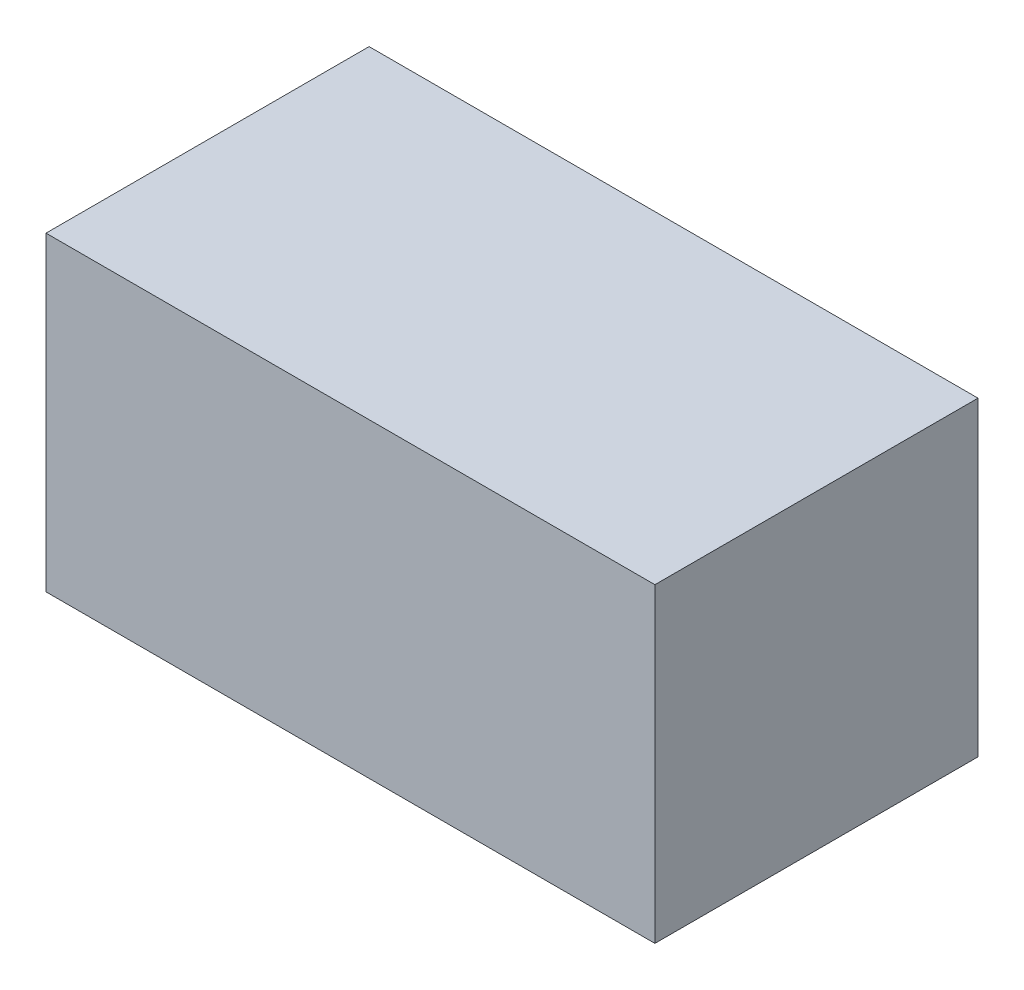
SolidWorks part; units mm, degrees
ref_plane "Front Plane" through (0, 0, 0) normal (0, 0, 1) x (1, 0, 0)
ref_plane "Top Plane" through (0, 0, 0) normal (0, 1, 0) x (1, 0, 0)
ref_plane "Right Plane" through (0, 0, 0) normal (1, 0, 0) x (0, 0, -1)
sketch "Sketch1" plane through (0, 0, 0) normal (0, 0, 1) x (1, 0, 0)
  line L1 (24.5, 12.5) -> (-24.5, 12.5)
  line L2 (24.5, 12.5) -> (24.5, -12.5)
  line L3 (24.5, -12.5) -> (-24.5, -12.5)
  line L4 (-24.5, 12.5) -> (-24.5, -12.5)
  line L5 (24.5, 12.5) -> (-24.5, -12.5) construction
  line L6 (24.5, -12.5) -> (-24.5, 12.5) construction
  point P0 (0, 0)
  dimension "D1" = 49
  dimension "D2" = 25
extrude "Boss-Extrude1" add sketch "Sketch1" along normal blind 26
